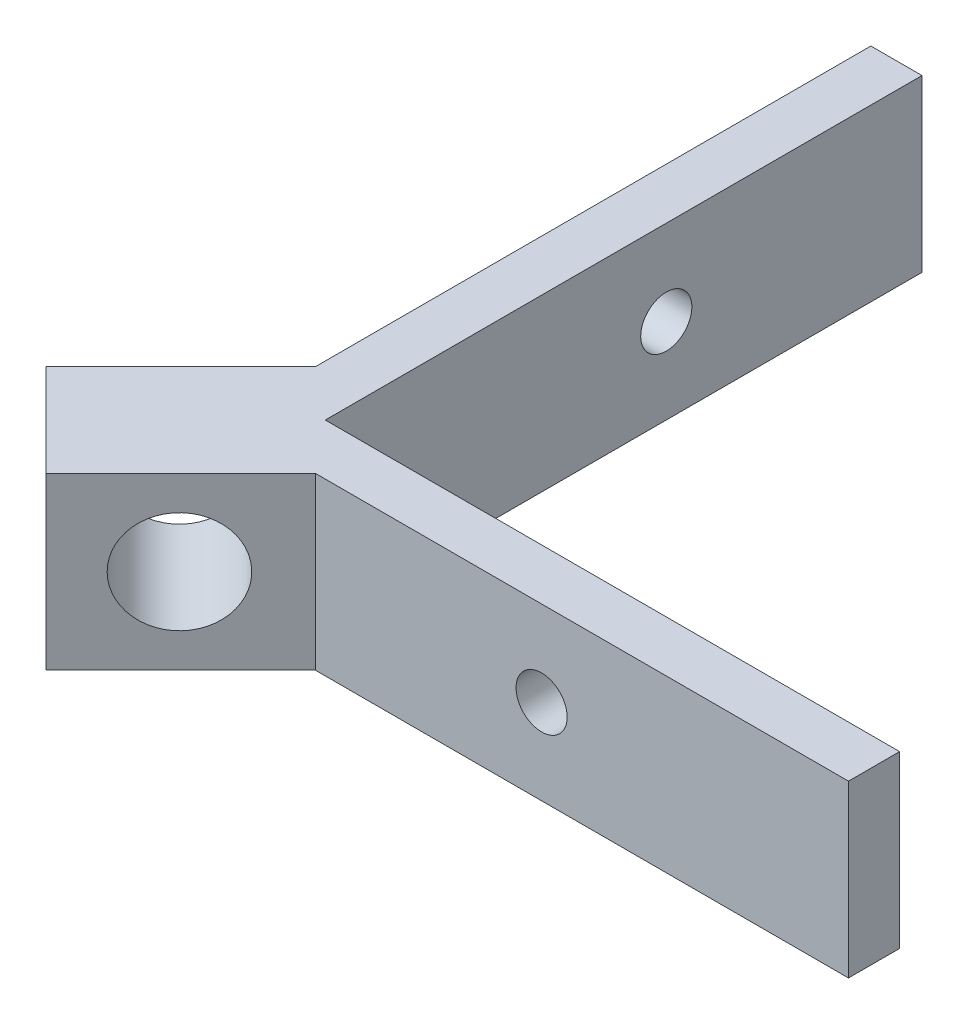
SolidWorks part; units mm, degrees
ref_plane "Front Plane" through (0, 0, 0) normal (0, 0, 1) x (1, 0, 0)
ref_plane "Top Plane" through (0, 0, 0) normal (0, 1, 0) x (1, 0, 0)
ref_plane "Right Plane" through (0, 0, 0) normal (1, 0, 0) x (0, 0, -1)
sketch "Sketch1" plane through (0, 0, 0) normal (0, 1, 0) x (1, 0, 0)
  line L2 (1.3117, 2.4152) -> (1.3117, 35)
  line L3 (1.3117, 35) -> (4.3117, 35)
  line L4 (4.3117, 0) -> (4.3117, 35)
  line L5 (4.3117, 0) -> (38, 0)
  line L7 (6.7269, -3) -> (38, -3)
  line L8 (38, 0) -> (38, -3)
  line L9 (-7.4152, 2.4152) -> (-10.9507, -1.1203)
  line L10 (-10.9507, -1.1203) -> (3.1914, -15.2625)
  line L11 (3.1914, -15.2625) -> (6.7269, -11.7269)
  line L13 (-7.4152, 2.4152) -> (1.3117, 2.4152)
  line L17 (6.7269, -3) -> (6.7269, -11.7269)
  dimension "D1" = 3
  dimension "D2" = 3
  dimension "D3" = 8.7269
  dimension "D4" = 8.7269
  dimension "D5" = 20
  dimension "D6" = 5
extrude "Boss-Extrude1" add sketch "Sketch1" along normal blind 10 contours L13 L2 L3 L4 L5 L8 L7 L17 L11 L10 L9
sketch "Sketch2" plane through (0, 10, 0) normal (0, 1, 0) x (1, 0, 0)
  line L0 (-7.4152, 2.4152) -> (-10.9507, -1.1203)
  line L1 (-7.4152, 2.4152) -> (6.7269, -11.7269)
  line L2 (-10.9507, -1.1203) -> (3.1914, -15.2625)
  line L3 (6.7269, -11.7269) -> (3.1914, -15.2625)
  dimension "D1" = 20
sketch "Sketch3" plane through (0, 0, 3) normal (0, 0, 1) x (1, 0, 0)
  circle A0 centre (20, 5) radius 1.5
extrude "Cut-Extrude1" cut sketch "Sketch3" against normal blind 30
sketch "Sketch4" plane through (1.3117, 0, 0) normal (-1, 0, 0) x (0, 0, 1)
  circle A0 centre (-20, 5) radius 1.5
  dimension "D1" = 3
extrude "Cut-Extrude2" cut sketch "Sketch4" against normal blind 30
sketch "Sketch8" plane through (0, 10, 0) normal (0, 1, 0) x (1, 0, 0)
  line L0 (1.3117, 2.4152) -> (-7.0652, -5.9617)
  line L1 (1.3117, 2.4152) -> (-5.798, 9.525)
  line L2 (-7.0652, -5.9617) -> (-14.1749, 1.1481)
  line L3 (-5.798, 9.525) -> (-14.1749, 1.1481)
  line L4 (6.7269, -3) -> (-1.1721, -10.899)
  line L5 (6.7269, -3) -> (12.4361, -8.7092)
  line L6 (-1.1721, -10.899) -> (4.5371, -16.6082)
  line L7 (12.4361, -8.7092) -> (4.5371, -16.6082)
  line L8 (-10.9507, -1.1203) -> (3.1914, -15.2625) construction
extrude "Cut-Extrude5" cut sketch "Sketch8" against normal blind 30
sketch "Sketch9" plane through (-0.5517, 0, -0.5517) normal (-0.7071, 0, -0.7071) x (-0.7071, 0, 0.7071)
  circle A0 centre (3, 5) radius 3
extrude "Cut-Extrude6" cut sketch "Sketch9" against normal blind 30
